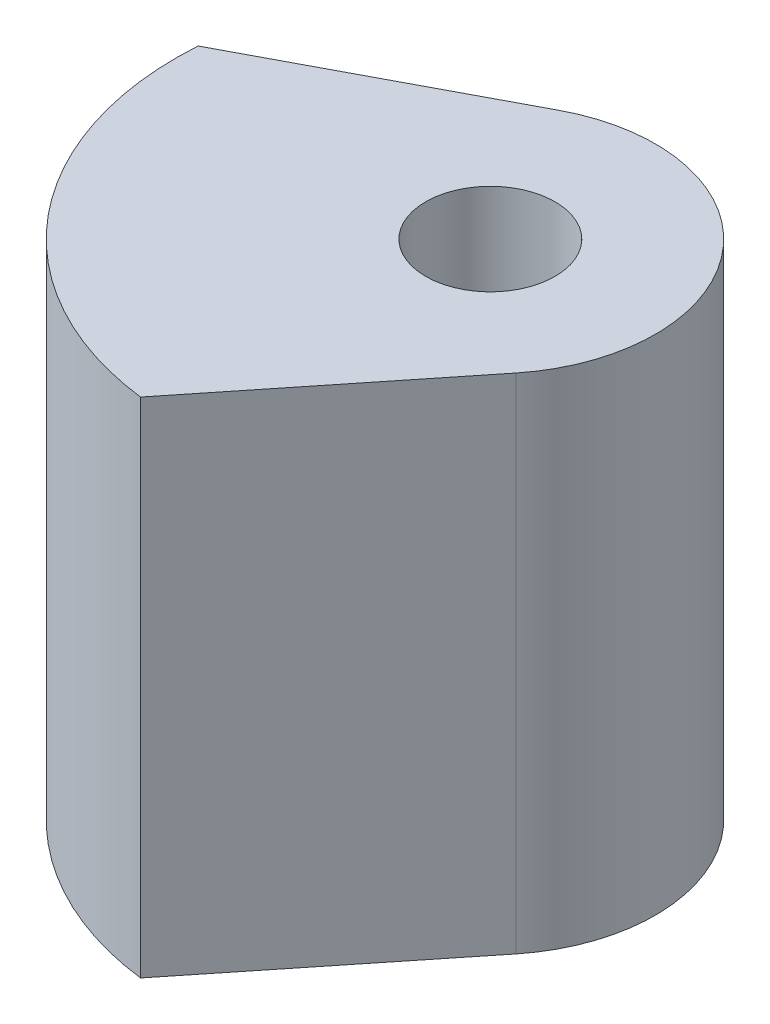
SolidWorks part; units mm, degrees
ref_plane "Front Plane" through (0, 0, 0) normal (0, 0, 1) x (1, 0, 0)
ref_plane "Top Plane" through (0, 0, 0) normal (0, 1, 0) x (1, 0, 0)
ref_plane "Right Plane" through (0, 0, 0) normal (1, 0, 0) x (0, 0, -1)
sketch "Sketch1" plane through (0, 0, 0) normal (0, 1, 0) x (1, 0, 0)
  line L0 (-14.667, -4.3386) -> (18.6449, 6.3999) construction
  dimension "D1" = 35
sketch "Sketch2" plane through (0, 0, 0) normal (0, 1, 0) x (1, 0, 0)
  line L0 (-3.4814, -4.3333) -> (-1.4905, -1.8456)
  line L1 (-3.9461, 1.124) -> (-6.7634, -0.3643)
  line L3 (-1.0292, 1.3627) -> (-9.699, -7.2243) construction
  circle A0 centre (-3.0269, -0.616) radius 0.7713
  arc A1 (-1.4905, -1.8456) -> (-3.9461, 1.124) centre (-3.0269, -0.616) ccw
  arc A2 (-6.7634, -0.3643) -> (-3.4814, -4.3333) centre (-3.0269, -0.616) ccw
  point P2 (-6.8634, -0.3576)
  point P6 (-3.4774, -4.3333)
  point P7 (0, 0)
  point P9 (-3.0269, -0.616)
  point P13 (-6.8282, -0.6907)
extrude "Boss-Extrude1" add sketch "Sketch2" along normal blind 6
